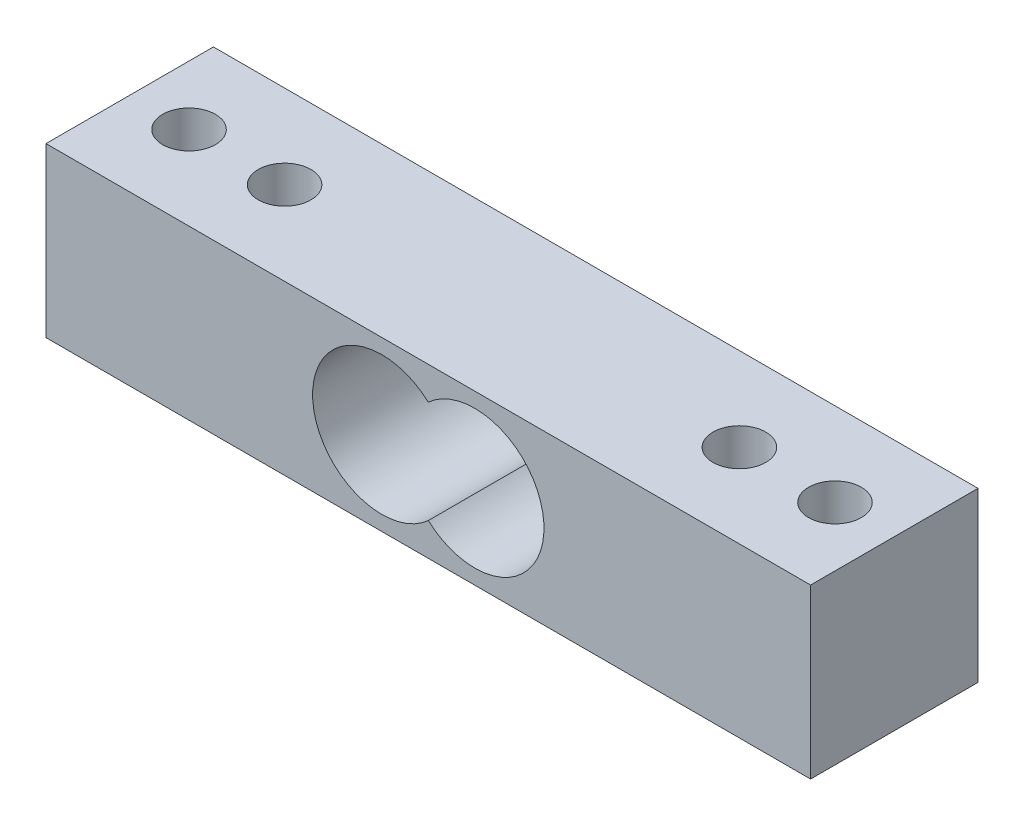
SolidWorks part; units mm, degrees
ref_plane "Front Plane" through (0, 0, 0) normal (0, 0, 1) x (1, 0, 0)
ref_plane "Top Plane" through (0, 0, 0) normal (0, 1, 0) x (1, 0, 0)
ref_plane "Right Plane" through (0, 0, 0) normal (1, 0, 0) x (0, 0, -1)
sketch "Sketch1" plane through (0, 0, 0) normal (0, 1, 0) x (1, 0, 0)
  line L1 (-29, -6.35) -> (29, -6.35)
  line L2 (-29, -6.35) -> (-29, 6.35)
  line L3 (-29, 6.35) -> (29, 6.35)
  line L4 (29, -6.35) -> (29, 6.35)
  line L5 (-29, -6.35) -> (29, 6.35) construction
  line L6 (-29, 6.35) -> (29, -6.35) construction
  circle A0 centre (-24.5, 0) radius 2
  circle A1 centre (-17.25, 0) radius 2
  circle A3 centre (24.5, 0) radius 2
  circle A4 centre (17.25, 0) radius 2
  point P0 (0, 0)
  dimension "D7" = 4
  dimension "D8" = 4
  dimension "D9" = 4
  dimension "D10" = 4
  dimension "D1" = 58
  dimension "D2" = 12.7
  dimension "D3" = 17.25
  dimension "D4" = 17.25
  dimension "D5" = 7.25
  dimension "D6" = 7.25
extrude "Boss-Extrude1" add sketch "Sketch1" along normal blind 12.75
sketch "Sketch2" plane through (0, 0, 6.35) normal (0, 0, 1) x (1, 0, 0)
  line L10 (-29, 0) -> (29, 0)
  line L11 (29, 0) -> (29, 12.75)
  line L12 (29, 12.75) -> (-29, 12.75)
  line L13 (-29, 12.75) -> (-29, 0)
  line L14 (-29, 0) -> (29, 0)
  line L15 (29, 0) -> (29, 12.75)
  line L16 (29, 12.75) -> (-29, 12.75)
  line L17 (-29, 12.75) -> (-29, 0)
  arc A0 (0, 10.2656) -> (0, 2.4844) centre (-3.525, 6.375) ccw
  arc A3 (0, 2.4844) -> (0, 10.2656) centre (3.525, 6.375) ccw
  point P0 (0, 6.375)
  point P9 (29, 6.375)
  dimension "D6" = 10.5
  dimension "D2" = 0
extrude "Cut-Extrude2" cut sketch "Sketch2" against normal through all both and the other way through all contours A0 A3
